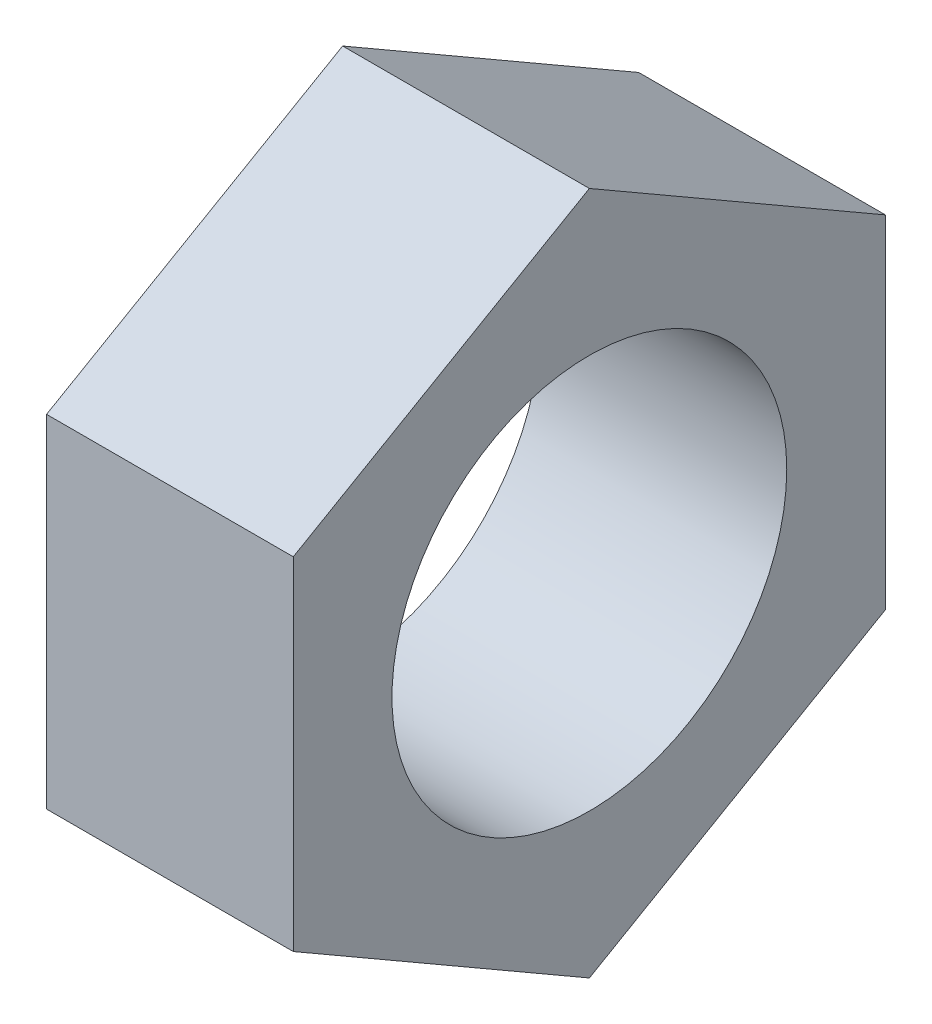
SolidWorks part; units mm, degrees
ref_plane "前视基准面" through (0, 0, 0) normal (0, 0, 1) x (1, 0, 0)
ref_plane "上视基准面" through (0, 0, 0) normal (0, 1, 0) x (1, 0, 0)
ref_plane "右视基准面" through (0, 0, 0) normal (1, 0, 0) x (0, 0, -1)
sketch "草图1" plane through (0, 0, 0) normal (1, 0, 0) x (0, 0, -1)
  line L0 (0, 6.9282) -> (-6, 3.4641)
  line L1 (4, -2.3094) -> (4, 2.3094)
  line L2 (4, 2.3094) -> (0, 4.6188)
  line L3 (0, 4.6188) -> (-4, 2.3094)
  line L4 (-4, 2.3094) -> (-4, -2.3094)
  line L5 (-4, -2.3094) -> (0, -4.6188)
  line L6 (0, -4.6188) -> (4, -2.3094)
  line L7 (-6, 3.4641) -> (-6, -3.4641)
  line L8 (-6, -3.4641) -> (0, -6.9282)
  line L9 (0, -6.9282) -> (6, -3.4641)
  line L10 (6, -3.4641) -> (6, 3.4641)
  line L11 (6, 3.4641) -> (0, 6.9282)
  circle A0 centre (0, 0) radius 4 construction
  circle A1 centre (0, 0) radius 4
  dimension "D1" = 8
  dimension "D2" = 8
  dimension "D3" = 2
extrude "凸台-拉伸1" add sketch "草图1" along normal blind 5 contours L10 L11 L0 L7 L8 L9 L6 L5 L4 L3 L2 L1 | A1 L3 L4 | A1 L4 L5 | A1 L5 L6 | A1 L6 L1 | A1 L1 L2 | A1 L2 L3
